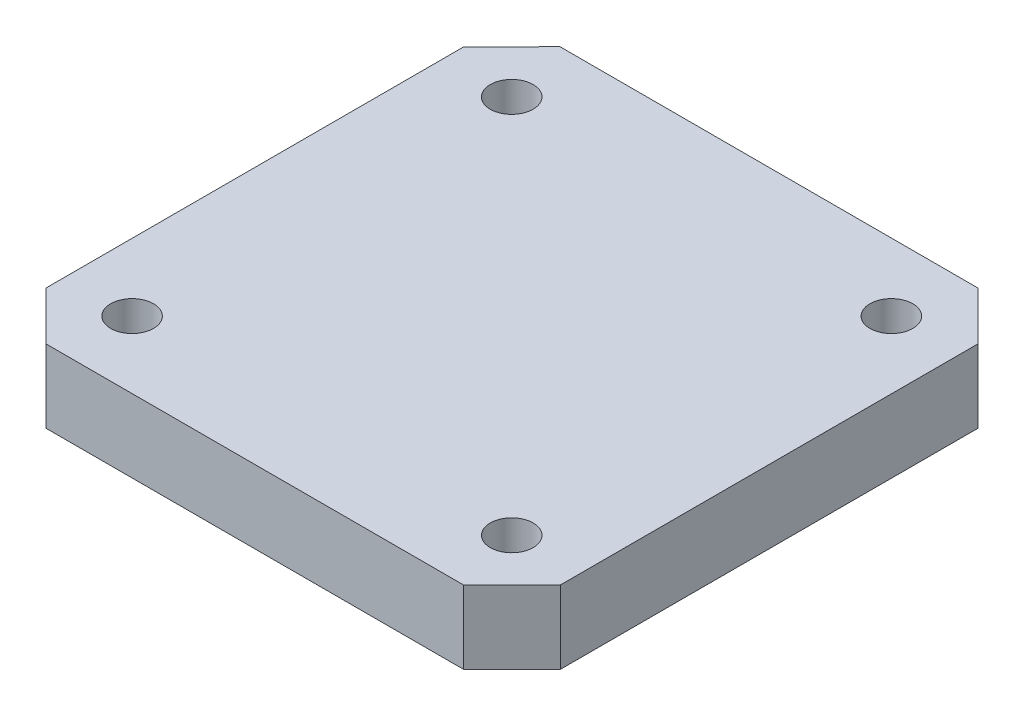
SolidWorks part; units mm, degrees
ref_plane "Front Plane" through (0, 0, 0) normal (0, 0, 1) x (1, 0, 0)
ref_plane "Top Plane" through (0, 0, 0) normal (0, 1, 0) x (1, 0, 0)
ref_plane "Right Plane" through (0, 0, 0) normal (1, 0, 0) x (0, 0, -1)
sketch "Sketch1" plane through (0, 0, 0) normal (0, 1, 0) x (1, 0, 0)
  line L0 (0, 38.0077) -> (3.9098, 42)
  line L1 (0, 0) -> (42, 0)
  line L2 (0, 0) -> (0, 42)
  line L3 (0, 42) -> (42, 42)
  line L4 (42, 0) -> (42, 42)
  line L5 (38.0433, 42) -> (42, 38.0541)
  line L6 (0, 0) -> (3.9512, 0) construction
  line L7 (0, 0) -> (0, 3.9512) construction
  line L8 (0, 3.9512) -> (3.9512, 0)
  line L9 (42, 0) -> (42, 3.9512) construction
  line L10 (42, 0) -> (38.0488, 0) construction
  line L11 (38.0488, 0) -> (42, 3.9512)
extrude "Boss-Extrude1" add sketch "Sketch1" along normal blind 5.969 contours L1 L11 L4 L5 L3 L0 L2 L8
sketch "Sketch2" plane through (0, 5.969, 0) normal (0, 1, 0) x (1, 0, 0)
  line L0 (0, 20.9794) -> (42, 20.9794) construction
  line L1 (0, 3.9512) -> (0, 38.0077) construction
  line L2 (42, 3.9512) -> (42, 38.0541) construction
  line L3 (20.9766, 42) -> (20.9766, 0) construction
  line L4 (3.9098, 42) -> (38.0433, 42) construction
  line L5 (3.9512, 0) -> (38.0488, 0) construction
  line L6 (36.5, 20.9794) -> (5.5, 20.9794) construction
  line L7 (5.5, 5.4794) -> (5.5, 36.4794) construction
  line L8 (36.5, 36.4794) -> (36.5, 5.4794) construction
  circle A0 centre (5.5, 36.4794) radius 1.75
  circle A1 centre (36.5, 36.4794) radius 1.75
  circle A2 centre (36.5, 5.4794) radius 1.75
  circle A3 centre (5.5, 5.4794) radius 1.75
  point P15 (21, 20.9794)
  point P17 (5.5, 20.9794)
  point P21 (36.5, 20.9794)
extrude "Cut-Extrude1" cut sketch "Sketch2" against normal blind 5.969
